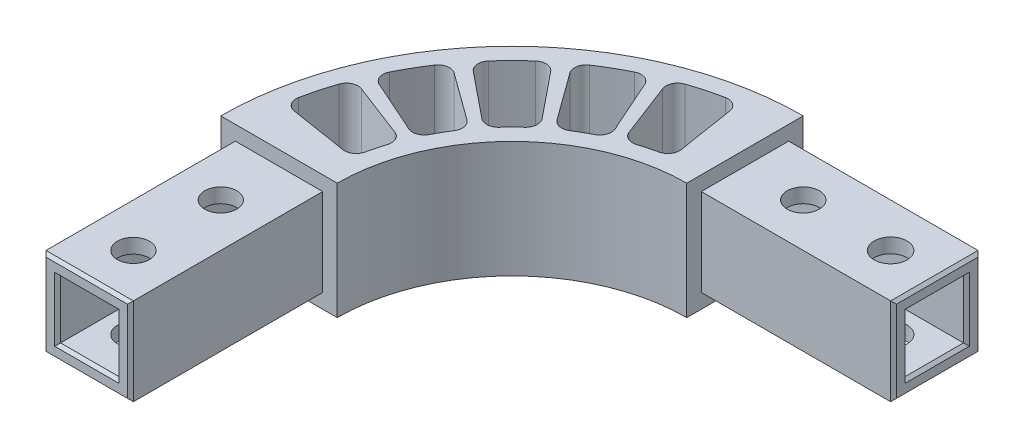
SolidWorks part; units mm, degrees
material "PA Type 6"
ref_plane "Front Plane" through (0, 0, 0) normal (0, 0, 1) x (1, 0, 0)
ref_plane "Top Plane" through (0, 0, 0) normal (0, 1, 0) x (1, 0, 0)
ref_plane "Right Plane" through (0, 0, 0) normal (1, 0, 0) x (0, 0, -1)
sketch "Sketch1" plane through (0, 0, 0) normal (0, 1, 0) x (1, 0, 0)
  line L0 (0, 68.9384) -> (0, -62.3869) construction
  line L1 (-91.3383, 0) -> (61.1848, 0) construction
  line L2 (0, 50) -> (0, 30)
  line L3 (-50, 0) -> (-30, 0)
  arc A0 (0, 50) -> (-50, 0) centre (0, 0) ccw
  arc A1 (0, 30) -> (-30, 0) centre (0, 0) ccw
  dimension "D1" = 100
  dimension "D2" = 60
extrude "Boss-Extrude1" add sketch "Sketch1" along normal blind 20
sketch "Sketch2" plane through (0, 0, 0) normal (0, 0, 1) x (1, 0, 0)
  line L0 (-50, 20) -> (-30, 0) construction
  line L1 (-30, 20) -> (-50, 0) construction
  line L3 (-47.5, 2.5) -> (-32.5, 2.5)
  line L4 (-47.5, 2.5) -> (-47.5, 17.5)
  line L5 (-47.5, 17.5) -> (-32.5, 17.5)
  line L6 (-32.5, 2.5) -> (-32.5, 17.5)
  line L7 (-47.5, 2.5) -> (-32.5, 17.5) construction
  line L8 (-47.5, 17.5) -> (-32.5, 2.5) construction
  point P8 (-40, 10)
  dimension "D1" = 15
extrude "Boss-Extrude2" add sketch "Sketch2" along normal blind 33
sketch "Sketch3" plane through (0, 0, 0) normal (1, 0, 0) x (0, 0, -1)
  line L0 (30, 20) -> (50, 0) construction
  line L1 (50, 20) -> (30, 0) construction
  line L3 (32.5, 2.5) -> (47.5, 2.5)
  line L4 (32.5, 2.5) -> (32.5, 17.5)
  line L5 (32.5, 17.5) -> (47.5, 17.5)
  line L6 (47.5, 2.5) -> (47.5, 17.5)
  line L7 (32.5, 2.5) -> (47.5, 17.5) construction
  line L8 (32.5, 17.5) -> (47.5, 2.5) construction
  point P8 (40, 10)
  dimension "D1" = 15
extrude "Boss-Extrude3" add sketch "Sketch3" along normal blind 33
sketch "Sketch4" plane through (0, 17.5, 0) normal (0, 1, 0) x (1, 0, 0)
  line L0 (-40, -33) -> (-40, 35.2645) construction
  line L1 (-32.5, -33) -> (-47.5, -33) construction
  line L2 (33, 40) -> (-33.6473, 40) construction
  line L3 (33, 47.5) -> (33, 32.5) construction
  line L4 (-57.4384, 0) -> (0, 0) construction
  line L5 (0, 0) -> (0, 52.2274) construction
  line L6 (10, 0) -> (10, 52.2274) construction
  line L7 (-57.4384, -10) -> (0, -10) construction
  line L8 (-57.4384, -25) -> (0, -25) construction
  line L9 (25, 0) -> (25, 52.2274) construction
  circle A0 centre (10, 40) radius 2.75
  circle A1 centre (25, 40) radius 2.825
  circle A2 centre (-40, -10) radius 2.75
  circle A3 centre (-40, -25) radius 2.75
  dimension "D5" = 5.5
  dimension "D6" = 5.5
  dimension "D7" = 5.65
  dimension "D8" = 5.5
  dimension "D1" = 10
  dimension "D2" = 10
  dimension "D3" = 15
  dimension "D4" = 15
extrude "Cut-Extrude1" cut sketch "Sketch4" against normal through all
sketch "Sketch5" plane through (0, 20, 0) normal (0, 1, 0) x (1, 0, 0)
  line L0 (0, 50) -> (0, 30) construction
  line L1 (-50, 0) -> (-30, 0) construction
  line L2 (0, 0) -> (-66.0694, 0) construction
  line L3 (0, 0) -> (-45.0318, 45.0318) construction
  line L4 (0, 0) -> (-37.5068, 46.317) construction
  line L5 (0, 0) -> (-47.2892, 38.2941) construction
  line L6 (-21.9902, 27.1557) -> (-28.2914, 34.937)
  line L7 (-27.1557, 21.9902) -> (-34.937, 28.2914)
  line L8 (-20.5389, 28.2693) -> (-26.4242, 36.3698)
  line L9 (-14.2125, 31.9218) -> (-18.2851, 41.0689)
  line L10 (-12.5224, 32.6219) -> (-16.1106, 41.9696)
  line L11 (-5.4663, 34.5126) -> (-7.0326, 44.4021)
  line L14 (-3.6525, 34.7514) -> (-4.6991, 44.7093) [skipped]
  line L15 (3.6525, 34.7514) -> (4.6991, 44.7093) [skipped]
  line L16 (-31.9218, 14.2125) -> (-41.0689, 18.2851)
  line L17 (-28.2693, 20.5389) -> (-36.3698, 26.4242)
  line L18 (-34.5126, 5.4663) -> (-44.4021, 7.0326)
  line L19 (-32.6219, 12.5224) -> (-41.9696, 16.1106)
  line L22 (-34.7514, -3.6525) -> (-44.7093, -4.6991) [skipped]
  line L23 (-34.7514, 3.6525) -> (-44.7093, 4.6991) [skipped]
  arc A0 (0, 30) -> (-30, 0) centre (0, 0) ccw construction
  arc A1 (0, 50) -> (-50, 0) centre (0, 0) ccw construction
  arc A3 (-31.1722, 35.1752) -> (-35.1752, 31.1722) centre (0, 0) ccw
  arc A4 (-21.9902, 27.1557) -> (-22.1991, 24.4172) centre (-23.5445, 25.897) cw
  arc A5 (-22.1991, 24.4172) -> (-24.4172, 22.1991) centre (0, 0) ccw
  arc A6 (-27.1557, 21.9902) -> (-24.4172, 22.1991) centre (-25.897, 23.5445) ccw
  arc A7 (-34.937, 28.2914) -> (-35.1752, 31.1722) centre (-33.6784, 29.8457) cw
  arc A8 (-28.2914, 34.937) -> (-31.1722, 35.1752) centre (-29.8457, 33.6784) ccw
  arc A9 (-26.4242, 36.3698) -> (-25.9087, 39.214) centre (-24.8062, 37.5454) cw
  arc A10 (-20.5389, 28.2693) -> (-17.8396, 27.7623) centre (-18.9208, 29.4449) ccw
  arc A11 (-21.006, 42.0446) -> (-25.9087, 39.214) centre (0, 0) ccw
  arc A12 (-18.2851, 41.0689) -> (-21.006, 42.0446) centre (-20.1122, 40.2555) ccw
  arc A13 (-14.2125, 31.9218) -> (-15.1231, 29.3308) centre (-16.0396, 31.1084) cw
  arc A14 (-15.1231, 29.3308) -> (-17.8396, 27.7623) centre (0, 0) ccw
  arc A15 (-16.1106, 41.9696) -> (-14.8765, 44.5835) centre (-14.2435, 42.6863) cw
  arc A16 (-12.5224, 32.6219) -> (-10.0464, 31.4336) centre (-10.6552, 33.3387) ccw
  arc A17 (-9.4083, 46.0487) -> (-14.8765, 44.5835) centre (0, 0) ccw
  arc A18 (-7.0326, 44.4021) -> (-9.4083, 46.0487) centre (-9.008, 44.0892) ccw
  arc A19 (-5.4663, 34.5126) -> (-7.0164, 32.2455) centre (-7.4416, 34.1997) cw
  arc A20 (-7.0164, 32.2455) -> (-10.0464, 31.4336) centre (0, 0) ccw
  arc A27 (-4.6991, 44.7093) -> (-2.8305, 46.9147) centre (-2.7101, 44.9183) cw [skipped]
  arc A28 (2.8305, 46.9147) -> (-2.8305, 46.9147) centre (0, 0) ccw [skipped]
  arc A29 (4.6991, 44.7093) -> (2.8305, 46.9147) centre (2.7101, 44.9183) ccw [skipped]
  arc A30 (3.6525, 34.7514) -> (1.5684, 32.9627) centre (1.6635, 34.9604) cw [skipped]
  arc A31 (1.5684, 32.9627) -> (-1.5684, 32.9627) centre (0, 0) ccw [skipped]
  arc A32 (-3.6525, 34.7514) -> (-1.5684, 32.9627) centre (-1.6635, 34.9604) ccw [skipped]
  arc A33 (-41.0689, 18.2851) -> (-42.0446, 21.006) centre (-40.2555, 20.1122) cw
  arc A34 (-31.9218, 14.2125) -> (-29.3308, 15.1231) centre (-31.1084, 16.0396) ccw
  arc A35 (-39.214, 25.9087) -> (-42.0446, 21.006) centre (0, 0) ccw
  arc A36 (-36.3698, 26.4242) -> (-39.214, 25.9087) centre (-37.5454, 24.8062) ccw
  arc A37 (-28.2693, 20.5389) -> (-27.7623, 17.8396) centre (-29.4449, 18.9208) cw
  arc A38 (-27.7623, 17.8396) -> (-29.3308, 15.1231) centre (0, 0) ccw
  arc A39 (-44.4021, 7.0326) -> (-46.0487, 9.4083) centre (-44.0892, 9.008) cw
  arc A40 (-34.5126, 5.4663) -> (-32.2455, 7.0164) centre (-34.1997, 7.4416) ccw
  arc A41 (-44.5835, 14.8765) -> (-46.0487, 9.4083) centre (0, 0) ccw
  arc A42 (-41.9696, 16.1106) -> (-44.5835, 14.8765) centre (-42.6863, 14.2435) ccw
  arc A43 (-32.6219, 12.5224) -> (-31.4336, 10.0464) centre (-33.3387, 10.6552) cw
  arc A44 (-31.4336, 10.0464) -> (-32.2455, 7.0164) centre (0, 0) ccw
  arc A51 (-44.7093, -4.6991) -> (-46.9147, -2.8305) centre (-44.9183, -2.7101) cw [skipped]
  arc A52 (-46.9147, 2.8305) -> (-46.9147, -2.8305) centre (0, 0) ccw [skipped]
  arc A53 (-44.7093, 4.6991) -> (-46.9147, 2.8305) centre (-44.9183, 2.7101) ccw [skipped]
  arc A54 (-34.7514, 3.6525) -> (-32.9627, 1.5684) centre (-34.9604, 1.6635) cw [skipped]
  arc A55 (-32.9627, 1.5684) -> (-32.9627, -1.5684) centre (0, 0) ccw [skipped]
  arc A56 (-34.7514, -3.6525) -> (-32.9627, -1.5684) centre (-34.9604, -1.6635) ccw [skipped]
  point P19 (-20.7676, 25.6458)
  point P22 (-25.6458, 20.7676)
  point P25 (-36.5259, 29.5781)
  point P28 (-29.5781, 36.5259)
  point P67 (0, 0)
  point P113 (0, 0)
  dimension "D1" = 45
  dimension "D2" = 3
  dimension "D3" = 33
  dimension "D6" = 2
  dimension "D4" = 6
  dimension "D5" = 6
  dimension "D7" = 4
  dimension "D8" = 4
extrude "Cut-Extrude2" cut sketch "Sketch5" against normal through all
sketch "Sketch6" plane through (33, 0, 0) normal (1, 0, 0) x (0, 0, -1)
  line L0 (32.5, 17.5) -> (47.5, 2.5) construction
  line L1 (47.5, 17.5) -> (32.5, 2.5) construction
  line L3 (35, 5) -> (45, 5)
  line L4 (35, 5) -> (35, 15)
  line L5 (35, 15) -> (45, 15)
  line L6 (45, 5) -> (45, 15)
  line L7 (35, 5) -> (45, 15) construction
  line L8 (35, 15) -> (45, 5) construction
  point P8 (40, 10)
  dimension "D1" = 10
extrude "Cut-Extrude3" cut sketch "Sketch6" against normal blind 33
sketch "Sketch7" plane through (0, 0, 33) normal (0, 0, 1) x (1, 0, 0)
  line L0 (-47.5, 17.5) -> (-32.5, 2.5) construction
  line L1 (-32.5, 17.5) -> (-47.5, 2.5) construction
  line L3 (-45, 15) -> (-35, 15)
  line L4 (-45, 15) -> (-45, 5)
  line L5 (-45, 5) -> (-35, 5)
  line L6 (-35, 15) -> (-35, 5)
  line L7 (-45, 15) -> (-35, 5) construction
  line L8 (-45, 5) -> (-35, 15) construction
  point P8 (-40, 10)
  dimension "D1" = 10
extrude "Cut-Extrude4" cut sketch "Sketch7" against normal blind 33
chamfer "Chamfer1" distance 0.5 angle 45 16 edges at (33, 2.5, -40) (33, 10, -32.5) (33, 17.5, -40) (33, 10, -47.5) (33, 10, -35) (33, 5, -40) (33, 10, -45) (33, 15, -40) (-40, 2.5, 33) (-47.5, 10, 33) (-40, 17.5, 33) (-32.5, 10, 33) (-45, 10, 33) (-40, 5, 33) (-35, 10, 33) (-40, 15, 33)
